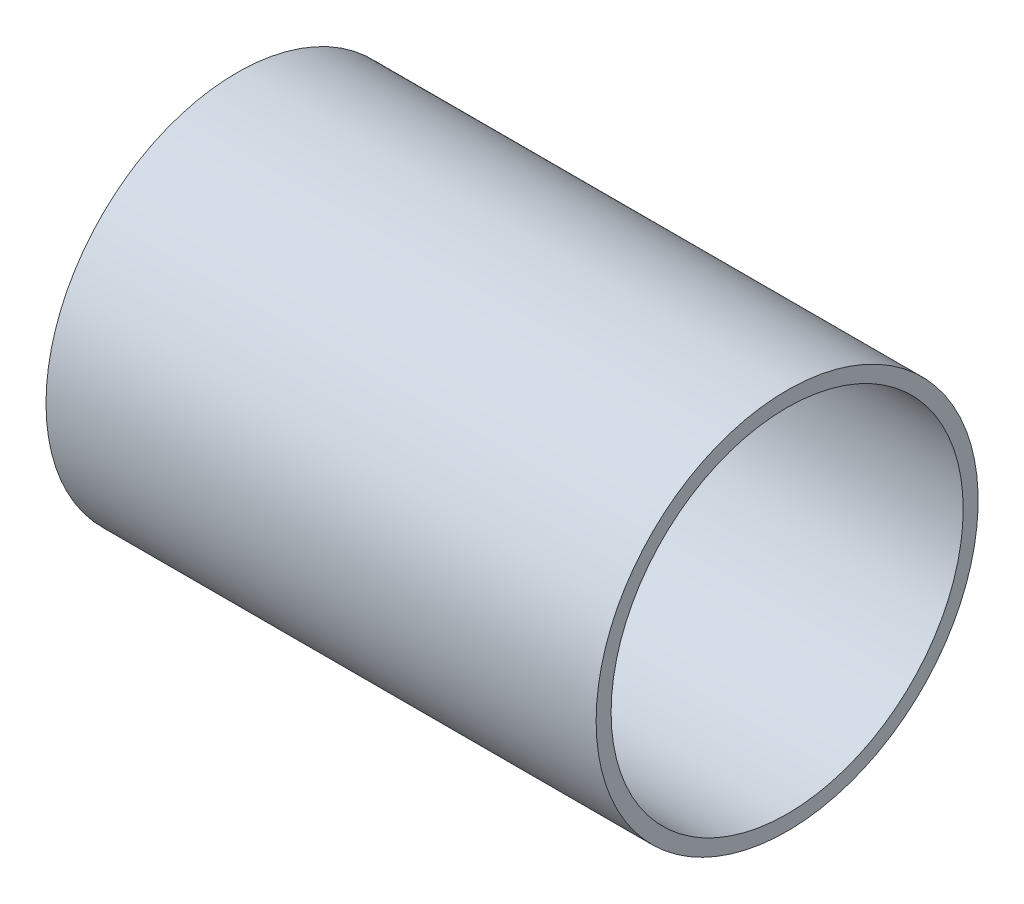
SolidWorks part; units mm, degrees
material "6061-T6 (SS)"
ref_plane "Front Plane" through (0, 0, 0) normal (0, 0, 1) x (1, 0, 0)
ref_plane "Top Plane" through (0, 0, 0) normal (0, 1, 0) x (1, 0, 0)
ref_plane "Right Plane" through (0, 0, 0) normal (1, 0, 0) x (0, 0, -1)
sketch "Sketch1" plane through (0, 0, 0) normal (0, 1, 0) x (1, 0, 0)
  line L0 (-72.894, 0) -> (78.2697, 0) construction
  line L1 (-22.86, 15.875) -> (-22.86, 14.6304)
  line L2 (-22.86, 15.875) -> (22.86, 15.875)
  line L3 (-22.86, 14.6304) -> (22.86, 14.6304)
  line L4 (22.86, 15.875) -> (22.86, 14.6304)
  line L5 (0, 0) -> (0, 14.6304) construction
  dimension "D1" = 31.75
  dimension "D2" = 1.2446
  dimension "D3" = 45.72
revolve "Revolve1" add sketch "Sketch1" angle 360 about L0
